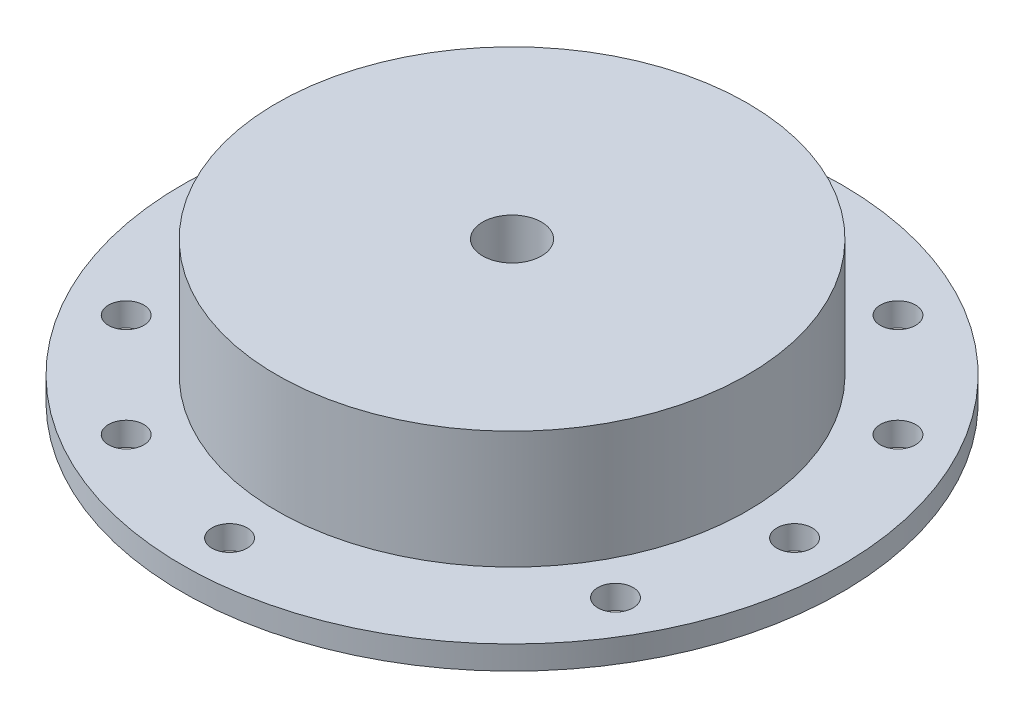
SolidWorks part; units mm, degrees
material "AISI 316 Annealed Stainless Steel Bar (SS)"
ref_plane "Front Plane" through (0, 0, 0) normal (0, 0, 1) x (1, 0, 0)
ref_plane "Top Plane" through (0, 0, 0) normal (0, 1, 0) x (1, 0, 0)
ref_plane "Right Plane" through (0, 0, 0) normal (1, 0, 0) x (0, 0, -1)
sketch "Sketch1" plane through (0, 0, 0) normal (0, 0, 1) x (1, 0, 0)
  line L0 (7.9375, 38.1) -> (7.9375, 11.1125)
  line L1 (38.1, 0) -> (88.9, 0)
  line L2 (88.9, 0) -> (88.9, 6.35)
  line L3 (88.9, 6.35) -> (63.5, 6.35)
  line L4 (63.5, 6.35) -> (63.5, 38.1)
  line L5 (63.5, 38.1) -> (7.9375, 38.1)
  line L6 (0, 0) -> (0, 33.4189) construction
  arc A0 (7.9375, 11.1125) -> (38.1, 0) centre (38.1, 46.4911) ccw
  dimension "D1" = 15.875
  dimension "D2" = 177.8
  dimension "D3" = 25.4
  dimension "D4" = 6.35
  dimension "D5" = 38.1
  dimension "D6" = 76.2
  dimension "D7" = 11.1125
revolve "Revolve1" add sketch "Sketch1" angle 360 about L6
sketch "Sketch3" plane through (0, 6.35, 0) normal (0, 1, 0) x (1, 0, 0)
  line L0 (0, 0) -> (0, -101.6) construction
  point P4 (0, -101.6)
  dimension "D1" = 101.6
hole_wizard "3/8 (0.375) Diameter Hole2" positions "Sketch4" profile "Sketch5" hole size "3/8" standard "ANSI Inch" end condition through all
sketch "Sketch4" plane through (0, 6.35, 0) normal (0, 1, 0) x (1, 0, 0)
  line L2 (0, 0) -> (0, -76.2) construction
  point P0 (0, -76.2)
  point P17 (0, 0)
  dimension "D1" = 76.2
sketch "Sketch5" plane through (0, 6.35, 76.2) normal (1, 0, 0) x (0, 0, 1)
  line L0 (0, 0) -> (0, 6.35)
  line L1 (0, 6.35) -> (4.7625, 6.35)
  line L2 (4.7625, 6.35) -> (4.7625, 0)
  line L5 (4.7625, 0) -> (0, 0)
  line L11 (0, -6.35) -> (0, 107.95) construction
  dimension "Thru Hole Dia." = 9.525
  dimension "Thru Hole Depth" = 6.35
pattern_circular "CirPattern2" count 12 over 360 about axis through (0, 0, 0) along (0, -1, 0) skipping 1 of "3/8 (0.375) Diameter Hole2"
